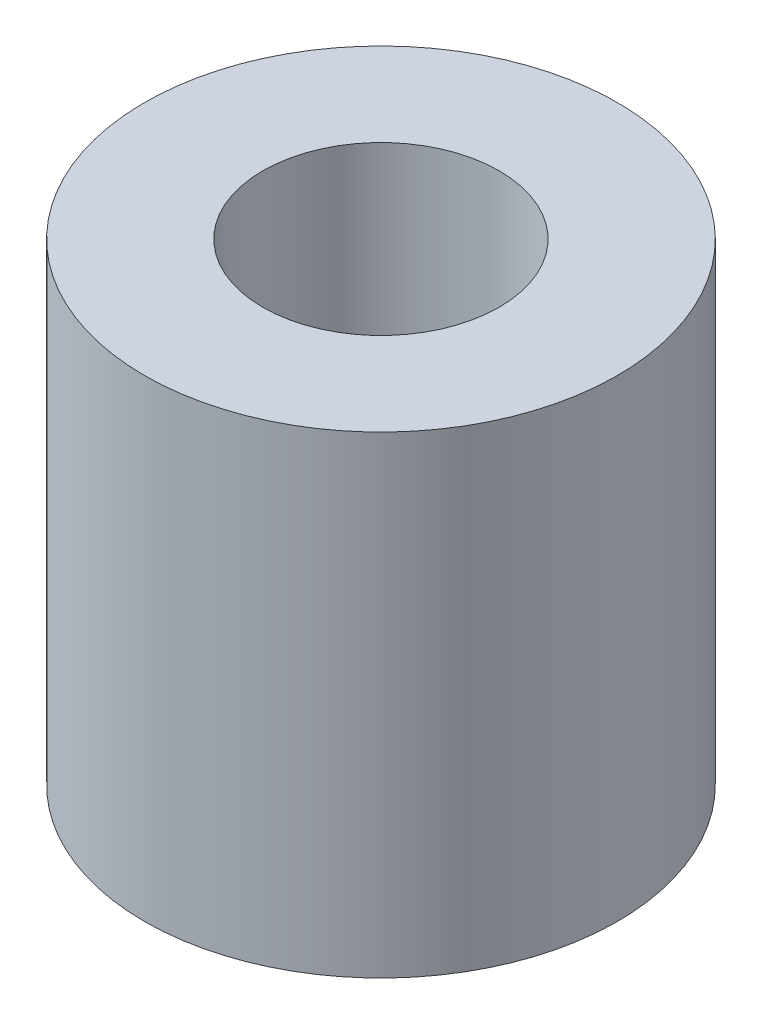
SolidWorks part; units mm, degrees
ref_plane "前视基准面" through (0, 0, 0) normal (0, 0, 1) x (1, 0, 0)
ref_plane "上视基准面" through (0, 0, 0) normal (0, 1, 0) x (1, 0, 0)
ref_plane "右视基准面" through (0, 0, 0) normal (1, 0, 0) x (0, 0, -1)
other "Configuration Table"
sketch "草图1" plane through (0, 0, 0) normal (0, 1, 0) x (1, 0, 0)
  circle A0 centre (0, 0) radius 1
  circle A1 centre (0, 0) radius 2
extrude "凸台-拉伸1" add sketch "草图1" along normal blind 4
